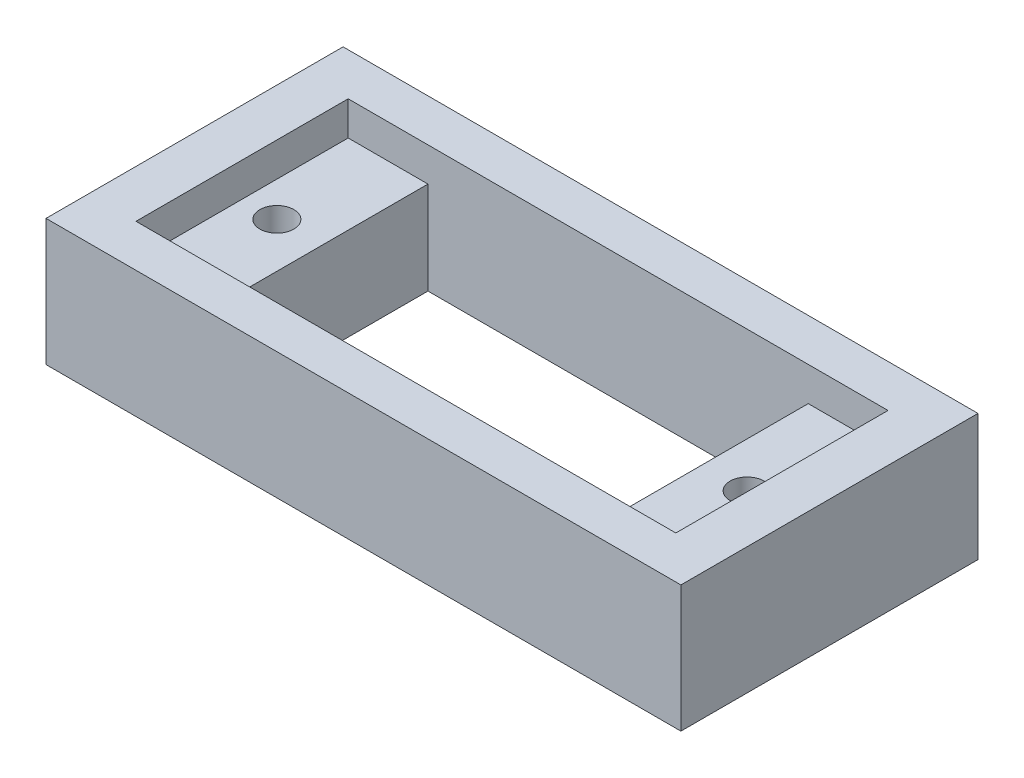
SolidWorks part; units mm, degrees
ref_plane "Front Plane" through (0, 0, 0) normal (0, 0, 1) x (1, 0, 0)
ref_plane "Top Plane" through (0, 0, 0) normal (0, 1, 0) x (1, 0, 0)
ref_plane "Right Plane" through (0, 0, 0) normal (1, 0, 0) x (0, 0, -1)
sketch "Sketch1" plane through (0, 0, 0) normal (0, 1, 0) x (1, 0, 0)
  line L0 (0, 14.5365) -> (0, -17.0646) construction
  line L1 (-33.4738, 0) -> (30.103, 0) construction
  line L2 (-18.7, 8.75) -> (-18.7, -8.75)
  line L3 (-11.2, 6.25) -> (11.2, 6.25)
  line L4 (-11.2, 6.25) -> (-11.2, -6.25)
  line L5 (-11.2, -6.25) -> (11.2, -6.25)
  line L6 (11.2, 6.25) -> (11.2, -6.25)
  line L7 (-11.2, 6.25) -> (11.2, -6.25) construction
  line L8 (-11.2, -6.25) -> (11.2, 6.25) construction
  line L9 (-18.7, -8.75) -> (18.7, -8.75)
  line L10 (18.7, -8.75) -> (18.7, 8.75)
  line L11 (18.7, 8.75) -> (-18.7, 8.75)
  circle A0 centre (13.85, 0) radius 1
  circle A1 centre (-13.85, 0) radius 1
  point P5 (0, 0)
  point P18 (18.7, 0)
  dimension "D3" = 2
  dimension "D1" = 12.5
  dimension "D2" = 22.4
  dimension "D4" = 27.7
  dimension "D5" = 2.5
  dimension "D6" = 7.5
  dimension "D7" = 7.5
  dimension "D8" = 2.5
extrude "Boss-Extrude1" add sketch "Sketch1" against normal blind 7.46
sketch "Sketch2" plane through (0, 0, 0) normal (0, 1, 0) x (1, 0, 0)
  line L0 (0, 6.25) -> (0, -6.25) construction
  line L1 (11.2, 6.25) -> (-11.2, 6.25) construction
  line L2 (-11.2, -6.25) -> (11.2, -6.25) construction
  line L3 (-18.7, 0) -> (18.7, 0) construction
  line L4 (-18.7, 8.75) -> (-18.7, -8.75) construction
  line L5 (18.7, -8.75) -> (18.7, 8.75) construction
  line L7 (-15.9, 6.25) -> (15.9, 6.25)
  line L8 (-15.9, 6.25) -> (-15.9, -6.25)
  line L9 (-15.9, -6.25) -> (15.9, -6.25)
  line L10 (15.9, 6.25) -> (15.9, -6.25)
  line L11 (-15.9, 6.25) -> (15.9, -6.25) construction
  line L12 (-15.9, -6.25) -> (15.9, 6.25) construction
  point P13 (0, 0)
  dimension "D1" = 12.5
  dimension "D2" = 31.8
extrude "Cut-Extrude1" cut sketch "Sketch2" against normal blind 2
